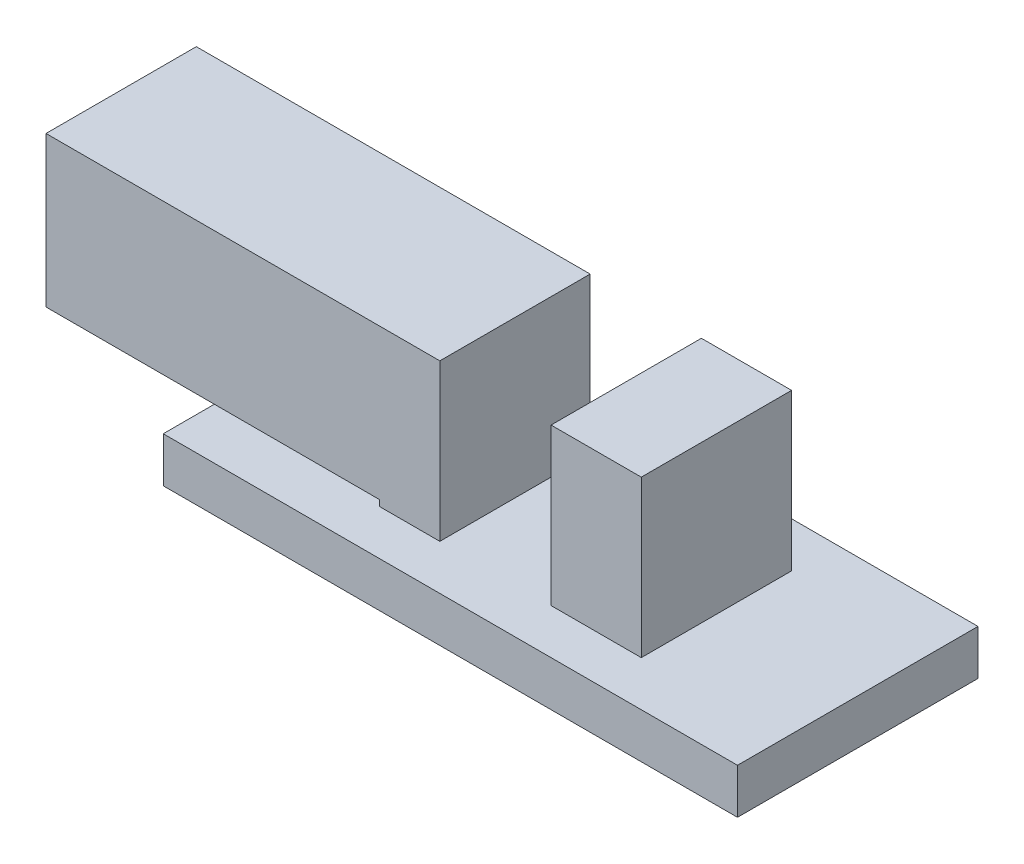
SolidWorks part; units mm, degrees
ref_plane "Front Plane" through (0, 0, 0) normal (0, 0, 1) x (1, 0, 0)
ref_plane "Top Plane" through (0, 0, 0) normal (0, 1, 0) x (1, 0, 0)
ref_plane "Right Plane" through (0, 0, 0) normal (1, 0, 0) x (0, 0, -1)
sketch "Sketch1" plane through (0, 0, 0) normal (0, 1, 0) x (1, 0, 0)
  line L1 (-95.5, 40) -> (95.5, 40)
  line L2 (-95.5, 40) -> (-95.5, -40)
  line L3 (-95.5, -40) -> (95.5, -40)
  line L4 (95.5, 40) -> (95.5, -40)
  line L5 (-95.5, 40) -> (95.5, -40) construction
  line L6 (-95.5, -40) -> (95.5, 40) construction
  point P0 (0, 0)
  dimension "D1" = 191
  dimension "D2" = 80
extrude "Boss-Extrude1" add sketch "Sketch1" along normal blind 15
sketch "Sketch2" plane through (0, 15, 0) normal (0, 1, 0) x (1, 0, 0)
  line L1 (-38.5, 25) -> (-18.5, 25)
  line L2 (-38.5, 25) -> (-38.5, -25)
  line L3 (-38.5, -25) -> (-18.5, -25)
  line L4 (-18.5, 25) -> (-18.5, -25)
  line L5 (-38.5, 25) -> (-18.5, -25) construction
  line L6 (-38.5, -25) -> (-18.5, 25) construction
  line L7 (18.5, 25) -> (48.5, 25)
  line L8 (18.5, 25) -> (18.5, -25)
  line L9 (18.5, -25) -> (48.5, -25)
  line L10 (48.5, 25) -> (48.5, -25)
  line L11 (18.5, 25) -> (48.5, -25) construction
  line L12 (18.5, -25) -> (48.5, 25) construction
  line L14 (95.5, -40) -> (95.5, 40) construction
  point P0 (-28.5, 0)
  point P5 (33.5, 0)
  point P12 (0, 0)
  dimension "D1" = 47
  dimension "D2" = 20
  dimension "D3" = 37
  dimension "D4" = 30
  dimension "D5" = 50
  dimension "D6" = 50
extrude "Boss-Extrude2" add sketch "Sketch2" along normal blind 52
sketch "Sketch3" plane through (-38.5, 0, 0) normal (1, 0, 0) x (0, 0, -1)
  line L0 (25, 67) -> (25, 15) construction
  line L1 (-25, 67) -> (25, 67)
  line L2 (-25, 67) -> (-25, 17)
  line L3 (-25, 17) -> (25, 17)
  line L4 (25, 67) -> (25, 17)
  line L5 (-25, 67) -> (25, 17) construction
  line L6 (25, 67) -> (-25, 17) construction
  dimension "D1" = 50
extrude "Boss-Extrude3" add sketch "Sketch3" against normal blind 111
